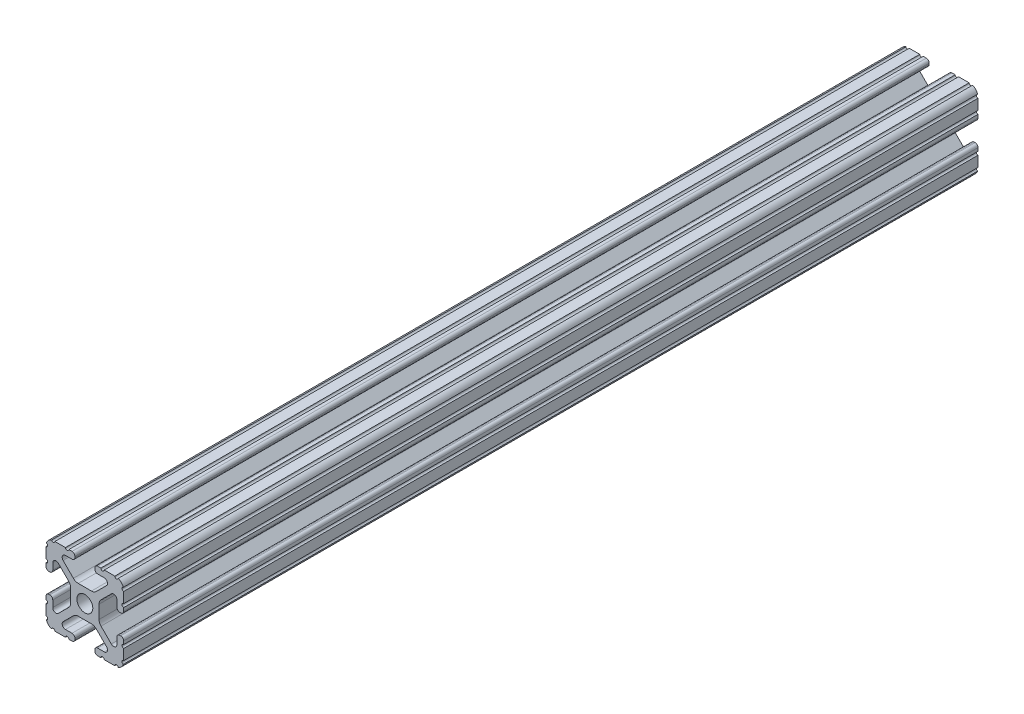
SolidWorks part; units mm, degrees
ref_plane "Front Plane" through (0, 0, 0) normal (0, 0, 1) x (1, 0, 0)
ref_plane "Top Plane" through (0, 0, 0) normal (0, 1, 0) x (1, 0, 0)
ref_plane "Right Plane" through (0, 0, 0) normal (1, 0, 0) x (0, 0, -1)
sketch "Sketch2" plane through (0, 0, 0) normal (0, 0, 1) x (1, 0, 0)
  line L0 (0, 12.7) -> (0, -12.7) construction
  line L1 (-12.7, 0) -> (12.7, 0) construction
  line L2 (3.2512, -12.7) -> (12.7, -12.7)
  line L3 (12.7, -12.7) -> (12.7, -3.2512)
  line L4 (3.2512, -12.7) -> (3.2512, -10.4902)
  line L5 (3.2512, -10.4902) -> (8.9276, -10.4902)
  line L6 (8.9276, -10.4902) -> (3.0856, -4.6482)
  line L7 (0, 0) -> (12.7, -12.7) construction
  line L8 (12.7, -3.2512) -> (10.4902, -3.2512)
  line L9 (10.4902, -3.2512) -> (10.4902, -8.9276)
  line L10 (10.4902, -8.9276) -> (4.6482, -3.0856)
  circle A0 centre (0, 0) radius 2.6035
  arc A1 (6.3485, -10.4902) -> (7.1039, -8.6665) centre (6.3485, -9.4219) ccw construction
  point P8 (0, -4.6482)
  dimension "Center Hole Diameter" = 5.207
  dimension "Rail Height" = 25.4
  dimension "Rail Width" = 25.4
  dimension "T-Slot Width" = 6.5024
  dimension "Slot Inner Width" = 14.8336
  dimension "Thickness" = 2.2098
  dimension "Slot Depth" = 5.842
  dimension "D1" = 2.2098
sketch "Sketch3" plane through (0, 0, 0) normal (1, 0, 0) x (0, 0, -1)
  line L0 (-1524, -12.7) -> (1524, -12.7) construction
  line L1 (-1498.6, 0) -> (1498.6, 0) construction
  dimension "Length" = 3048
  dimension "D1" = 25.4
sketch "Sketch4" plane through (0, 0, 0) normal (0, 0, 1) x (1, 0, 0)
  line L0 (4.1904, -12.7) -> (10.1173, -12.7)
  line L1 (3.2512, -12.7) -> (12.7, -12.7) construction
  line L2 (3.2512, -12.7) -> (3.2512, -10.4902) construction
  line L3 (3.2512, -10.4902) -> (8.9276, -10.4902) construction
  line L4 (3.2512, -11.4294) -> (3.2512, -11.7608)
  line L5 (4.1904, -10.4902) -> (6.3485, -10.4902)
  line L6 (0, -4.6482) -> (2.164, -4.6482)
  line L7 (8.9276, -10.4902) -> (3.0856, -4.6482) construction
  line L8 (3.7373, -5.2999) -> (7.1039, -8.6665)
  line L9 (12.7, -12.7) -> (12.7, -3.2512) construction
  line L10 (10.4902, -8.9276) -> (4.6482, -3.0856) construction
  line L11 (10.4902, -3.2512) -> (10.4902, -8.9276) construction
  line L12 (10.4902, -6.3485) -> (10.4902, -4.1904)
  line L13 (12.7, -3.2512) -> (10.4902, -3.2512) construction
  line L14 (11.4294, -3.2512) -> (11.7608, -3.2512)
  line L15 (12.7, -4.1904) -> (12.7, -10.1173)
  line L16 (8.6665, -7.1039) -> (5.2999, -3.7373)
  line L17 (4.6482, 0) -> (4.6482, -2.164)
  line L18 (-12.7, 0) -> (12.7, 0) construction
  line L19 (0, -4.6482) -> (0, -2.6035)
  line L20 (0, 12.7) -> (0, -12.7) construction
  line L21 (4.6482, 0) -> (2.6035, 0)
  arc A0 (3.2512, -11.7608) -> (4.1904, -12.7) centre (4.1904, -11.7608) ccw
  arc A2 (3.2512, -11.4294) -> (4.1904, -10.4902) centre (4.1904, -11.4294) cw
  arc A3 (6.3485, -10.4902) -> (7.1039, -8.6665) centre (6.3485, -9.4219) ccw
  arc A4 (2.164, -4.6482) -> (3.7373, -5.2999) centre (2.164, -6.8732) cw
  arc A5 (10.1173, -12.7) -> (12.7, -10.1173) centre (10.1173, -10.1173) ccw
  arc A6 (8.6665, -7.1039) -> (10.4902, -6.3485) centre (9.4219, -6.3485) ccw
  arc A7 (10.4902, -4.1904) -> (11.4294, -3.2512) centre (11.4294, -4.1904) cw
  arc A8 (11.7608, -3.2512) -> (12.7, -4.1904) centre (11.7608, -4.1904) cw
  arc A9 (5.2999, -3.7373) -> (4.6482, -2.164) centre (6.8732, -2.164) cw
  circle A10 centre (0, 0) radius 2.6035 construction
  arc A11 (0, -2.6035) -> (2.6035, 0) centre (0, 0) ccw
  dimension "D1" = 2.5827
  dimension "D2" = 2.225
  dimension "D3" = 0.9392
extrude "Boss-Extrude1" add sketch "Sketch4" along normal mid plane 3048
sketch "Sketch5" plane through (0, 0, 0) normal (0, 0, 1) x (1, 0, 0)
  line L0 (3.2512, -12.7) -> (12.7, -12.7) construction
  line L1 (4.1904, -10.4902) -> (6.3485, -10.4902) construction
  line L3 (0, 0) -> (12.7, -12.7) construction
  line L4 (6.3485, -10.4902) -> (6.3485, -12.7) construction
  line L5 (8.9276, -10.4902) -> (3.0856, -4.6482) construction
  circle A0 centre (10.3562, -12.7) radius 0.5524
  circle A1 centre (5.796, -12.7) radius 0.5524
  circle A2 centre (12.7, -10.3562) radius 0.5524
  circle A3 centre (12.7, -5.796) radius 0.5524
  point P10 (5.2694, -10.4902)
  point P12 (9.4219, -6.3485)
  dimension "D1" = 1.1049
extrude "Cut-Extrude1" cut sketch "Sketch5" against normal through all both and the other way through all
mirror "Mirror1" about plane through (0, 0, 0) normal (1, 0, 0) of bodies 137 134
mirror "Mirror2" about plane through (0, 0, 0) normal (0, 1, 0) of bodies 135
sketch "Sketch8" plane through (0, 0, 0) normal (0, 1, 0) x (1, 0, 0)
  line L0 (-12.58, 1524) -> (-12.58, -1524) construction
  line L1 (-25.28, 1536.7) -> (25.28, 1536.7)
  line L2 (-25.28, 1536.7) -> (-25.28, -1244.6)
  line L3 (-25.28, -1244.6) -> (25.28, -1244.6)
  line L4 (25.28, 1536.7) -> (25.28, -1244.6)
  line L5 (12.58, 1524) -> (12.58, -1524) construction
  line L7 (-6.3485, -1524) -> (-9.8037, -1524) construction
  dimension "D1" = 12.7
  dimension "D2" = 12.7
  dimension "D3" = 12.7
  dimension "D4" = 279.4
extrude "Cut-Extrude2" cut sketch "Sketch8" against normal through all both and the other way through all
equation "\"D1@Boss-Extrude1\"=\"Length@Sketch3\""
equation "\"D1@Sketch2\"=\"Thickness@Sketch2\""
equation "\"D2@Sketch4\"=\"Slot Inner Width@Sketch2\"*0.15"
equation "\"D1@Sketch4\"=\"D3@Sketch4\"*2.75"
equation "\"D3@Sketch4\"=\"Thickness@Sketch2\"*0.425"
equation "\"D1@Sketch5\"=\"Thickness@Sketch2\"*0.5"
